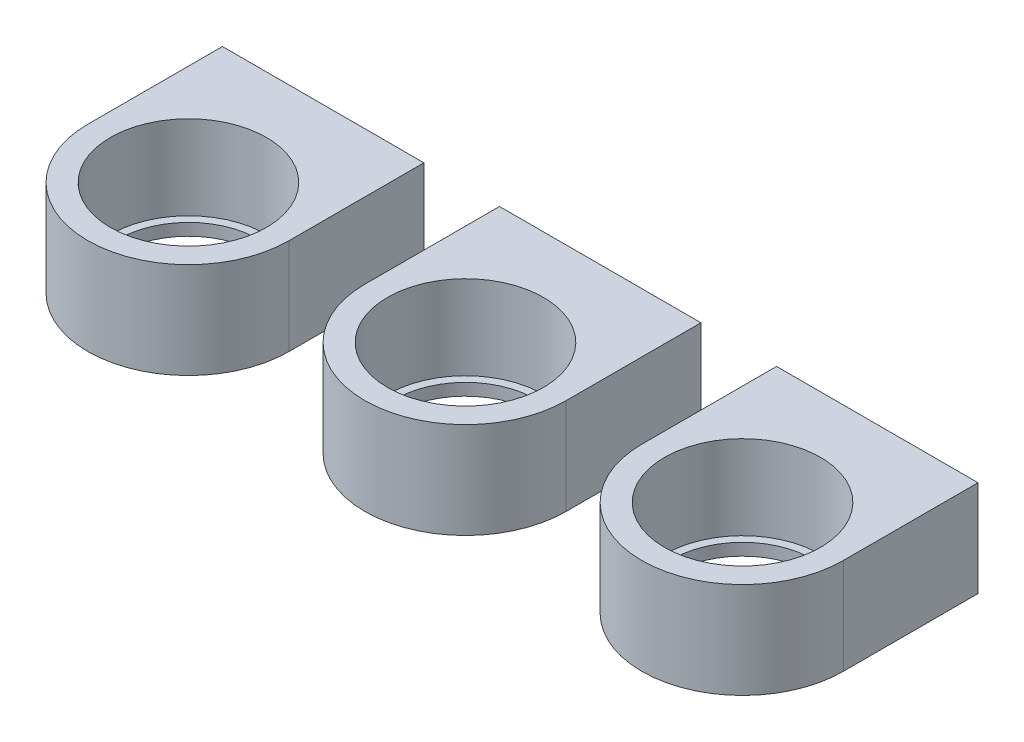
SolidWorks part; units mm, degrees
material "6061-T6 (SS)"
ref_plane "Front Plane" through (0, 0, 0) normal (0, 0, 1) x (1, 0, 0)
ref_plane "Top Plane" through (0, 0, 0) normal (0, 1, 0) x (1, 0, 0)
ref_plane "Right Plane" through (0, 0, 0) normal (1, 0, 0) x (0, 0, -1)
sketch "Sketch1" plane through (0, 0, 0) normal (0, 1, 0) x (1, 0, 0)
  line L0 (-13.3188, 0) -> (-13.3188, 13.3188)
  line L2 (13.3188, 13.3188) -> (13.3188, 0)
  line L3 (-13.3188, 13.3188) -> (-13.3188, 17.8188)
  line L4 (-13.3188, 17.8188) -> (13.3188, 17.8188)
  line L5 (13.3188, 17.8188) -> (13.3188, 13.3188)
  arc A1 (-13.3188, 0) -> (13.3188, 0) centre (0, 0) ccw
  circle A3 centre (0, 0) radius 9.25
extrude "Boss-Extrude1" add sketch "Sketch1" along normal blind 12.7
sketch "Sketch2" plane through (0, 12.7, 0) normal (0, 1, 0) x (1, 0, 0)
  circle A0 centre (0, 0) radius 10.3187
  dimension "D1" = 20.6375
extrude "Cut-Extrude1" cut sketch "Sketch2" against normal blind 11.1125
ref_plane "Plane1" through (18.3188, 0, 0) normal (1, 0, 0) x (0, 0, -1)
ref_plane "Plane2" through (-18.3188, 0, 0) normal (-1, 0, 0) x (0, 0, 1)
sketch "Sketch3" plane through (0, 0, -17.8188) normal (0, 0, -1) x (-1, 0, 0)
  line L0 (0, 0) -> (-18.3188, 0)
  line L1 (-18.3188, 6.985) -> (-18.3188, -6.985) construction
  line L2 (-18.3188, 0) -> (-18.3188, -1.4783)
  line L3 (-18.3188, -1.4783) -> (18.3188, -1.4783)
  line L4 (18.3188, -6.985) -> (18.3188, 6.985) construction
  line L5 (18.3188, -1.4783) -> (18.3188, 0)
  line L6 (18.3188, 0) -> (0, 0)
extrude "Boss-Extrude2" add sketch "Sketch3" against normal blind 40
mirror "Mirror2" about plane through (-18.3188, 0, 0) normal (-1, 0, 0) of bodies 110
mirror "Mirror4" about plane through (18.3188, 0, 0) normal (1, 0, 0) of bodies 111
sketch "Sketch4" plane through (49.9563, 0, 0) normal (1, 0, 0) x (0, 0, -1)
  line L1 (31.762, 15.2589) -> (-27.5844, 15.2589)
  line L2 (31.762, 15.2589) -> (31.762, -6.2377)
  line L3 (31.762, -6.2377) -> (-27.5844, -6.2377)
  line L4 (-27.5844, 15.2589) -> (-27.5844, -6.2377)
  line L5 (31.762, 15.2589) -> (-27.5844, -6.2377) construction
  line L6 (31.762, -6.2377) -> (-27.5844, 15.2589) construction
  point P0 (2.0888, 4.5106)
extrude "Cut-Extrude2" cut sketch "Sketch4" along normal blind 45
sketch "Sketch5" plane through (0, 0, -17.8188) normal (0, 0, -1) x (-1, 0, 0)
  line L1 (54.9563, 0) -> (-49.9563, 0)
  line L2 (54.9563, 0) -> (54.9563, -1.4783)
  line L3 (54.9563, -1.4783) -> (-49.9563, -1.4783)
  line L4 (-49.9563, 0) -> (-49.9563, -1.4783)
extrude "Cut-Extrude3" cut sketch "Sketch5" against normal blind 45
